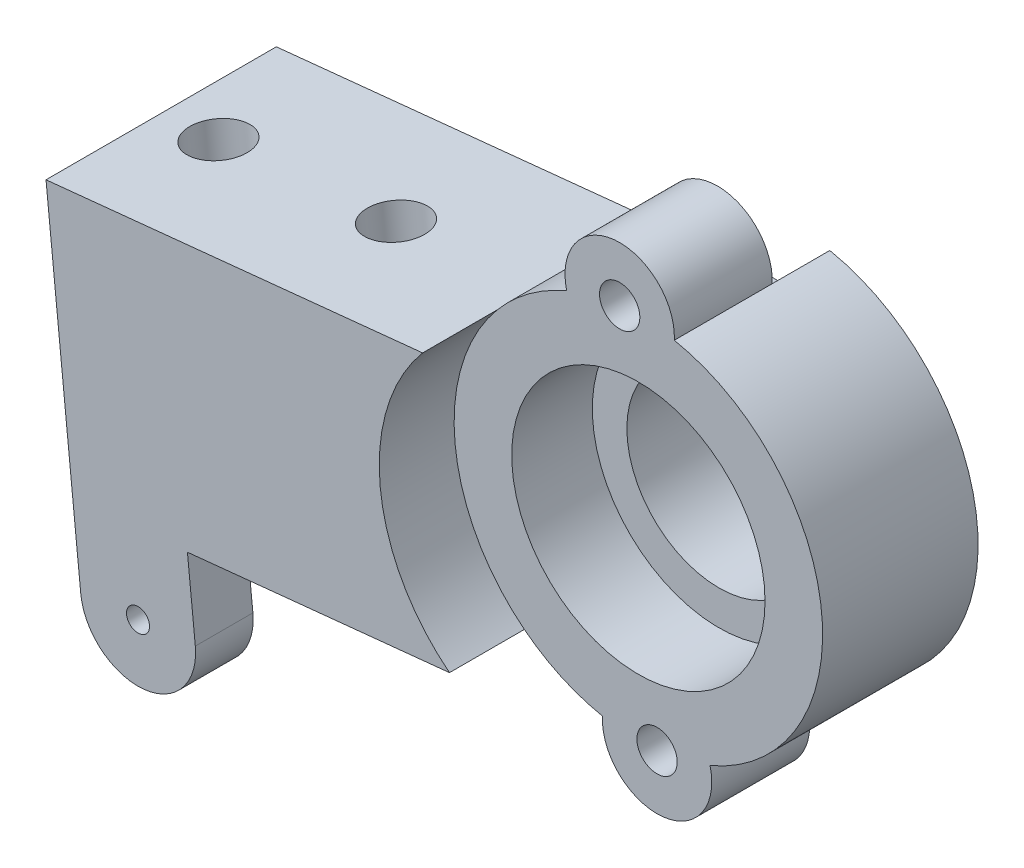
SolidWorks part; units mm, degrees
ref_plane "Front Plane" through (0, 0, 0) normal (0, 0, 1) x (1, 0, 0)
ref_plane "Top Plane" through (0, 0, 0) normal (0, 1, 0) x (1, 0, 0)
ref_plane "Right Plane" through (0, 0, 0) normal (1, 0, 0) x (0, 0, -1)
sketch "Sketch1" plane through (0, 0, 0) normal (0, 0, 1) x (1, 0, 0)
  circle A0 centre (0, 0) radius 11
  circle A1 centre (0, 0) radius 16
  dimension "D1" = 22
  dimension "D2" = 5
extrude "Boss-Extrude1" add sketch "Sketch1" along normal blind 7
ref_plane "Plane1" through (0, 0, 3.5) normal (0, 0, -1) x (-1, 0, 0)
sketch "Sketch2" plane through (0, 0, 3.5) normal (0, 0, 1) x (1, 0, 0)
  line L0 (0, 0) -> (-27.9086, -2.8448) construction
  line L1 (-12.2331, 10.3126) -> (-44.9394, 6.9788)
  line L2 (-44.9394, 6.9788) -> (-42.607, -15.9026)
  line L3 (-42.607, -15.9026) -> (-9.9008, -12.5688)
  circle A0 centre (0, 0) radius 16 construction
  arc A1 (-12.2331, 10.3126) -> (-9.9008, -12.5688) centre (0, 0) ccw
  dimension "D1" = 11.5
  dimension "D2" = 11.5
  dimension "D3" = 28
extrude "Boss-Extrude2" add sketch "Sketch2" against normal blind 10 and the other way blind 10
sketch "Sketch3" plane through (-43.7732, -4.4619, 0) normal (-0.9948, -0.1014, 0) x (0, 0, 1)
  line L0 (-6.5, 11.5) -> (13.5, -11.5) construction
  line L2 (10, 6.5) -> (-3, 6.5)
  line L3 (10, 6.5) -> (10, -6.5)
  line L4 (10, -6.5) -> (-3, -6.5)
  line L5 (-3, 6.5) -> (-3, -6.5)
  line L6 (10, 6.5) -> (-3, -6.5) construction
  line L7 (10, -6.5) -> (-3, 6.5) construction
  point P4 (3.5, 0)
  dimension "D1" = 13
  dimension "D2" = 13
extrude "Cut-Extrude1" cut sketch "Sketch3" against normal blind 26
sketch "Sketch8" plane through (0, 0, 0) normal (0, 0, -1) x (-1, 0, 0)
  circle A0 centre (0, 0) radius 16
  circle A1 centre (0, 0) radius 8
  circle A3 centre (0, 0) radius 11 construction
  dimension "D1" = 3
extrude "Boss-Extrude5" add sketch "Sketch8" along normal up to surface (6.5 mm away) up to face at (-28.6327, -2.9186, -6.5)
sketch "Sketch9" plane through (0, 0, -6.5) normal (0, 0, -1) x (-1, 0, 0)
  line L0 (42.607, -15.9026) -> (32.6586, -14.8886)
  line L1 (42.607, -15.9026) -> (9.9008, -12.5688) construction
  line L2 (32.6586, -14.8886) -> (31.9737, -21.607)
  line L3 (42.607, -15.9026) -> (41.9222, -22.6211)
  arc A0 (41.9222, -22.6211) -> (31.9737, -21.607) centre (36.9479, -22.1141) cw
  circle A1 centre (36.9479, -22.1141) radius 1
  dimension "D1" = 5
  dimension "D3" = 2
  dimension "D2" = 10
extrude "Boss-Extrude6" add sketch "Sketch9" against normal up to surface (20 mm away) up to face at (-28.6327, -2.9186, 13.5)
ref_plane "Plane2" through (0, 0, 3.5) normal (0, 0, 1) x (1, 0, 0)
sketch "Sketch10" plane through (0, 0, 3.5) normal (0, 0, 1) x (1, 0, 0)
  line L0 (-32.6586, -14.8886) -> (-42.607, -15.9026)
  line L4 (-12.2331, 10.3126) -> (-44.9394, 6.9788)
  line L5 (-44.9394, 6.9788) -> (-41.9222, -22.6211)
  line L6 (-31.9737, -21.607) -> (-32.6586, -14.8886)
  line L7 (-32.6586, -14.8886) -> (-9.9008, -12.5688)
  line L9 (-42.607, -15.9026) -> (-41.9222, -22.6211)
  line L10 (-31.9737, -21.607) -> (-32.6586, -14.8886)
  arc A2 (-12.2331, 10.3126) -> (-9.9008, -12.5688) centre (0, 0) ccw
  arc A3 (-41.9222, -22.6211) -> (-31.9737, -21.607) centre (-36.9479, -22.1141) ccw
  arc A5 (-41.9222, -22.6211) -> (-31.9737, -21.607) centre (-36.9479, -22.1141) ccw
  dimension "D1" = 0
extrude "Cut-Extrude3" cut sketch "Sketch10" against normal blind 5 and the other way blind 5
sketch "Sketch11" plane through (0, 0, 7) normal (0, 0, 1) x (1, 0, 0)
  line L0 (-2.2849, 22.416) -> (-1.6225, 15.9175)
  line L1 (-44.9394, 6.9788) -> (-41.9222, -22.6211) construction
  line L2 (1.445, -14.1765) -> (2.3915, -23.4619)
  arc A0 (6.2242, -14.7397) -> (-3.1222, -15.6924) centre (1.6225, -15.9175) cw
  arc A1 (-9.9008, -12.5688) -> (-12.2331, 10.3126) centre (0, 0) ccw construction
  arc A2 (-3.1222, -15.6924) -> (6.2242, -14.7397) centre (0, 0) ccw
  circle A3 centre (1.6225, -15.9175) radius 1.75 construction
  arc A4 (-1.6225, 15.9175) -> (-12.2331, 10.3126) centre (0, 0) ccw
  dimension "D1" = 3.5
  dimension "D2" = 3
extrude "Boss-Extrude7" add sketch "Sketch11" against normal offset from surface (8.5 mm away) 5 contours A2 A0
sketch "Sketch12" plane through (0, 0, 7) normal (0, 0, 1) x (1, 0, 0)
  arc A0 (6.2242, -14.7397) -> (-3.1222, -15.6924) centre (0, 0) cw construction
  arc A1 (-9.9008, -12.5688) -> (-3.1222, -15.6924) centre (0, 0) ccw construction
  circle A2 centre (1.6225, -15.9175) radius 1.75
  dimension "D1" = 3.5
extrude "Cut-Extrude4" cut sketch "Sketch12" against normal up to surface (13.5 mm away)
ref_plane "Plane3" through (0, 0, 0) normal (0.1014, -0.9948, 0) x (-0.9948, -0.1014, 0)
mirror "Mirror1" about plane through (0, 0, 0) normal (0.1014, -0.9948, 0) of "Boss-Extrude7", "Cut-Extrude4"
sketch "Sketch13" plane through (0, 0, -6.5) normal (0, 0, -1) x (-1, 0, 0)
  circle A0 centre (-1.6225, -15.9175) radius 4.75
  circle A1 centre (1.6225, 15.9175) radius 4.75
  arc A2 (6.2242, 14.7397) -> (-3.1222, 15.6924) centre (1.6225, 15.9175) ccw construction
  arc A3 (-6.2242, -14.7397) -> (3.1222, -15.6924) centre (-1.6225, -15.9175) ccw construction
extrude "Cut-Extrude5" cut sketch "Sketch13" against normal up to vertex (5 mm away) up to point (-3.1221, -15.6924, -1.5)
sketch "Sketch14" plane through (1.1662, -11.4407, 0) normal (0.1014, -0.9948, 0) x (0.9948, 0.1014, 0)
  circle A0 centre (-39, 3.5) radius 2.5
  circle A1 centre (-23.5, 3.5) radius 2.5
  dimension "D1" = 5
  dimension "D2" = 5
extrude "Cut-Extrude6" cut sketch "Sketch14" against normal up to surface (23 mm away) up to face at (-25.3156, 8.9791, 4.2)
